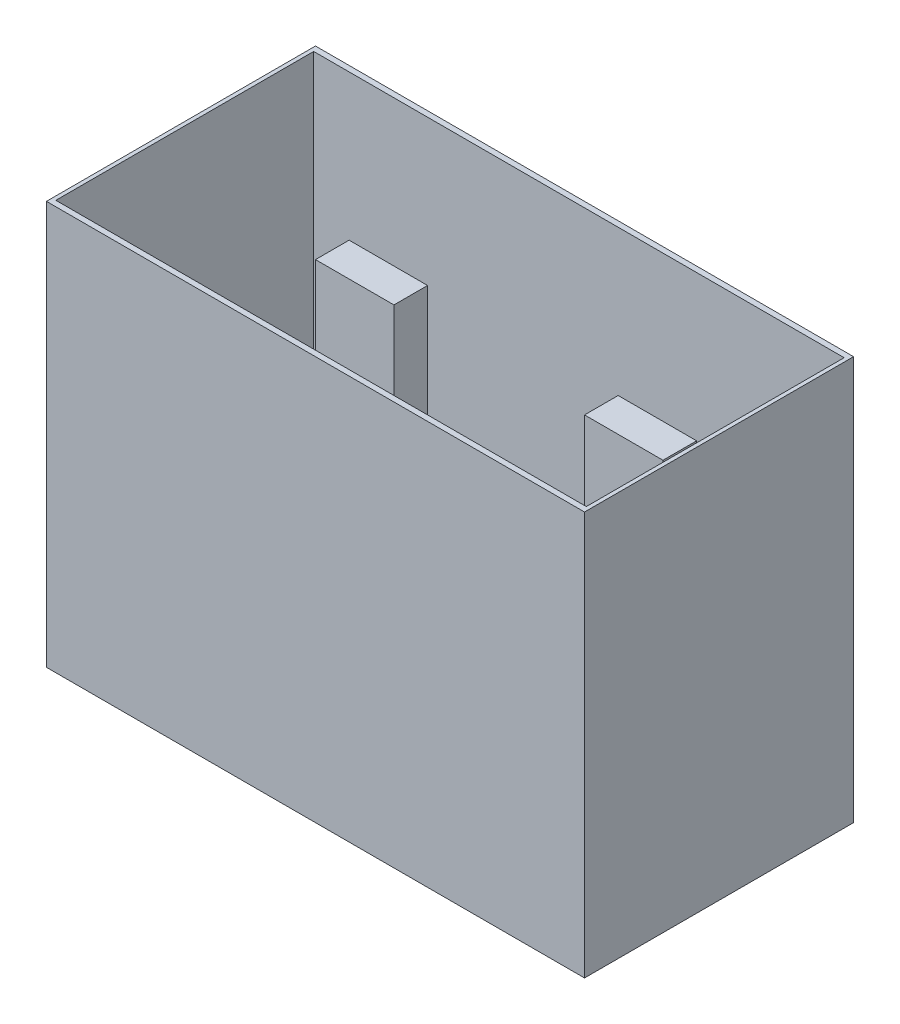
SolidWorks part; units mm, degrees
ref_plane "Front Plane" through (0, 0, 0) normal (0, 0, 1) x (1, 0, 0)
ref_plane "Top Plane" through (0, 0, 0) normal (0, 1, 0) x (1, 0, 0)
ref_plane "Right Plane" through (0, 0, 0) normal (1, 0, 0) x (0, 0, -1)
other "Bounding Box"
ref_plane "Default Plane" through (-292.1, 0, -139.7) normal (0, 1, 0) x (1, 0, 0)
sketch "Sketch1" plane through (0, 0, 0) normal (0, 1, 0) x (1, 0, 0)
  line L0 (-292.1, 0) -> (292.1, 0) construction
  line L1 (-292.1, 139.7) -> (292.1, 139.7)
  line L2 (-292.1, 139.7) -> (-292.1, -139.7)
  line L3 (-292.1, -139.7) -> (292.1, -139.7)
  line L4 (292.1, 139.7) -> (292.1, -139.7)
  line L5 (0, 139.7) -> (0, -139.7) construction
  point P8 (0, 0)
  dimension "D1" = 584.2
  dimension "D2" = 279.4
extrude "Boss-Extrude1" add sketch "Sketch1" along normal blind 6.35
sketch "Sketch2" plane through (0, 6.35, 0) normal (0, 1, 0) x (1, 0, 0)
  line L0 (-292.1, -139.7) -> (292.1, -139.7) construction
  line L1 (-241.3, -127) -> (-152.4, -127)
  line L2 (-241.3, -127) -> (-241.3, -88.9)
  line L3 (-241.3, -88.9) -> (-152.4, -88.9)
  line L4 (-152.4, -127) -> (-152.4, -88.9)
  line L5 (-241.3, -127) -> (-152.4, -88.9) construction
  line L6 (-241.3, -88.9) -> (-152.4, -127) construction
  line L7 (-292.1, 139.7) -> (-292.1, -139.7) construction
  point P0 (-196.85, -107.95)
  dimension "D1" = 38.1
  dimension "D2" = 88.9
  dimension "D3" = 12.7
  dimension "D4" = 50.8
extrude "Boss-Extrude2" add sketch "Sketch2" along normal blind 304.8 contours L2 L1 L4 L3
pattern_linear "LPattern1" count 2 spacing 304.8 along (1, 0, 0) of "Boss-Extrude2"
pattern_linear "LPattern2" count 2 spacing 215.9 along (0, 0, -1) of "Boss-Extrude2", "LPattern1"
sketch "Sketch3" plane through (0, 0, 0) normal (0, 1, 0) x (1, 0, 0)
  line L1 (-304.8, -152.4) -> (304.8, -152.4)
  line L2 (-304.8, -152.4) -> (-304.8, 152.4)
  line L3 (-304.8, 152.4) -> (304.8, 152.4)
  line L4 (304.8, -152.4) -> (304.8, 152.4)
  line L5 (-304.8, -152.4) -> (304.8, 152.4) construction
  line L6 (-304.8, 152.4) -> (304.8, -152.4) construction
  line L7 (-300.482, -146.05) -> (300.482, -146.05)
  line L8 (-300.482, -146.05) -> (-300.482, 146.05)
  line L9 (-300.482, 146.05) -> (300.482, 146.05)
  line L10 (300.482, -146.05) -> (300.482, 146.05)
  line L11 (-300.482, -146.05) -> (300.482, 146.05) construction
  line L12 (-300.482, 146.05) -> (300.482, -146.05) construction
  point P0 (0, 0)
  point P6 (0, 0)
  dimension "D1" = 609.6
  dimension "D2" = 304.8
  dimension "D3" = 292.1
  dimension "D4" = 600.964
extrude "Boss-Extrude3" add sketch "Sketch3" along normal blind 457.2 separate body
